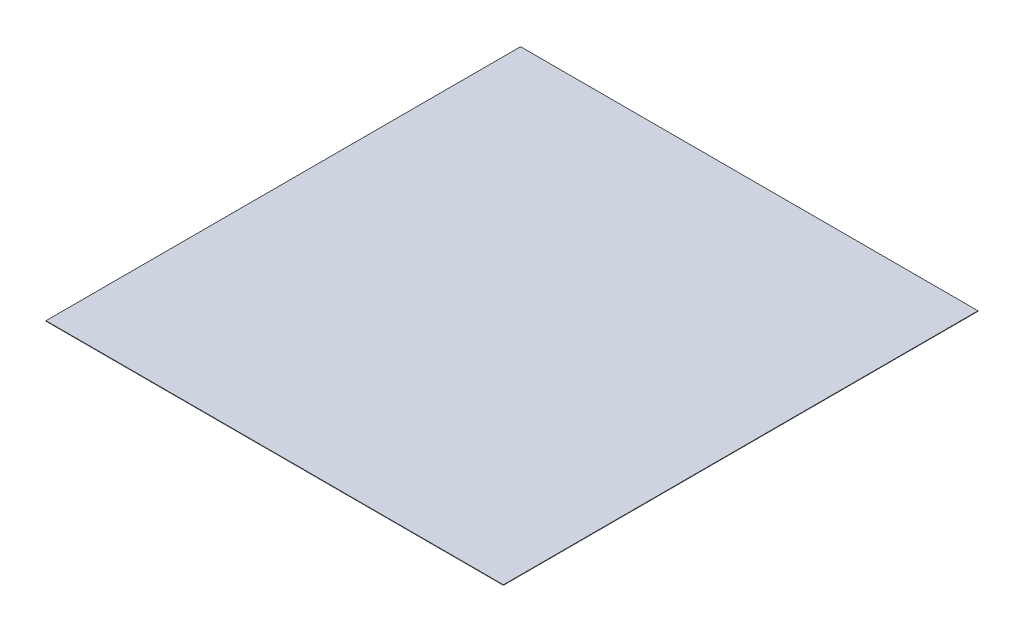
SolidWorks part; units mm, degrees
ref_plane "Спереди" through (0, 0, 0) normal (0, 0, 1) x (1, 0, 0)
ref_plane "Сверху" through (0, 0, 0) normal (0, 1, 0) x (1, 0, 0)
ref_plane "Справа" through (0, 0, 0) normal (1, 0, 0) x (0, 0, -1)
other "Configuration Table"
sketch "Эскиз1" plane through (0, 0, 0) normal (0, 1, 0) x (1, 0, 0)
  line L1 (500, 518.75) -> (-500, 518.75)
  line L2 (500, 518.75) -> (500, -518.75)
  line L3 (500, -518.75) -> (-500, -518.75)
  line L4 (-500, 518.75) -> (-500, -518.75)
  line L5 (500, 518.75) -> (-500, -518.75) construction
  line L6 (500, -518.75) -> (-500, 518.75) construction
  point P0 (0, 0)
extrude "Бобышка-Вытянуть1" add sketch "Эскиз1" along normal blind 1
